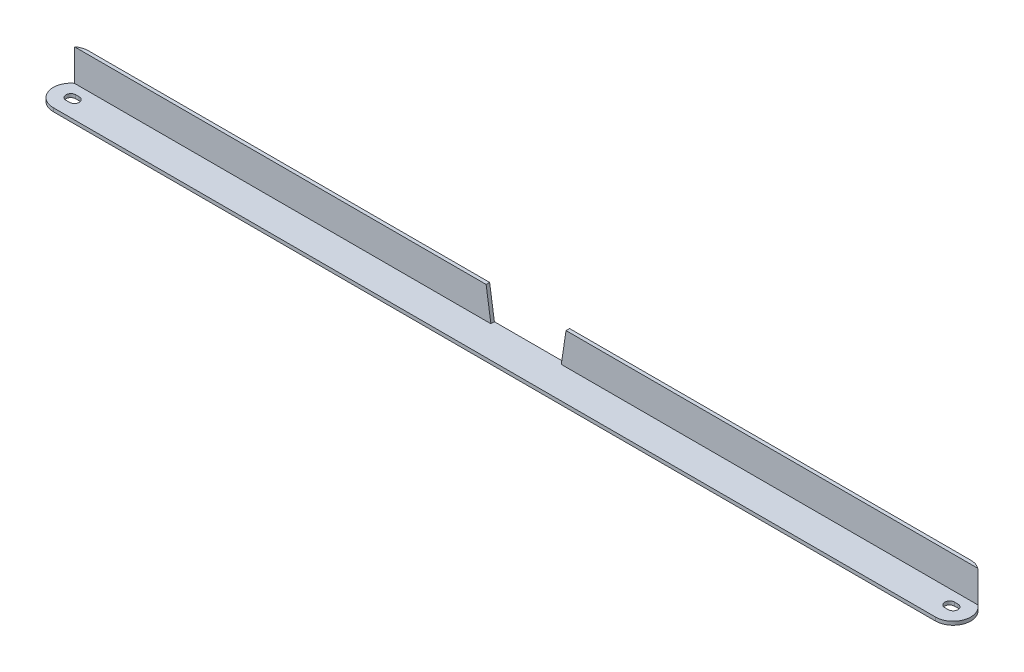
SolidWorks part; units mm, degrees
ref_plane "Front Plane" through (0, 0, 0) normal (0, 0, 1) x (1, 0, 0)
ref_plane "Top Plane" through (0, 0, 0) normal (0, 1, 0) x (1, 0, 0)
ref_plane "Right Plane" through (0, 0, 0) normal (1, 0, 0) x (0, 0, -1)
sketch "Sketch1" plane through (0, 0, 0) normal (1, 0, 0) x (0, 0, -1)
  line L0 (8, 10) -> (10, 10)
  line L1 (-10, 10) -> (10, 10) construction
  line L2 (-10, 10) -> (-10, -10) construction
  line L3 (-10, -10) -> (10, -10)
  line L4 (10, 10) -> (10, -10)
  line L5 (-10, 10) -> (10, -10) construction
  line L6 (-10, -10) -> (10, 10) construction
  line L7 (-10, 10) -> (8, 10) construction
  line L8 (-10, 10) -> (-10, -8) construction
  line L9 (-10, -8) -> (8, -8)
  line L10 (8, 10) -> (8, -8)
  line L11 (-10, -8) -> (-10, -10)
  point P0 (0, 0)
  dimension "D1" = 20
  dimension "D2" = 20
  dimension "D3" = 2
extrude "Boss-Extrude1" add sketch "Sketch1" along normal mid plane 540
sketch "Sketch2" plane through (0, 0, 0) normal (0, 1, 0) x (1, 0, 0)
  line L0 (0, 0) -> (249.65, 0) construction
  line L1 (248.65, 0) -> (250.65, 0) construction
  line L2 (250.65, -10) -> (270, -10)
  line L3 (248.65, 2.75) -> (250.65, 2.75)
  line L4 (248.65, -2.75) -> (250.65, -2.75)
  line L7 (270, 8) -> (270, -10) construction
  line L8 (270, -10) -> (270, 10)
  line L9 (270, 10) -> (250.65, 10)
  arc A0 (248.65, 2.75) -> (248.65, -2.75) centre (248.65, 0) ccw
  arc A1 (250.65, -2.75) -> (250.65, 2.75) centre (250.65, 0) ccw
  arc A2 (250.65, -10) -> (250.65, 10) centre (250.65, 0) ccw
  point P7 (249.65, 0)
  dimension "D1" = 249.65
  dimension "D2" = 2
extrude "Cut-Extrude1" cut sketch "Sketch2" against normal through all both and the other way through all contours L3 A1 L4 A0 | A2 L9 L8 L2
mirror "Mirror1" about plane through (0, 0, 0) normal (1, 0, 0) of "Cut-Extrude1"
sketch "Sketch3" plane through (0, 0, -8) normal (0, 0, 1) x (1, 0, 0)
  line L0 (-20, -8) -> (20, -8)
  line L1 (256.65, -8) -> (-256.65, -8) construction
  line L2 (20, -8) -> (22.706, 10)
  line L3 (256.65, 10) -> (-256.65, 10) construction
  line L4 (22.706, 10) -> (-22.706, 10)
  line L5 (0, -11) -> (0, 11) construction
  line L6 (-20, -8) -> (-22.706, 10)
  point P11 (0, 10)
  point P12 (0, -8)
  dimension "D1" = 20
extrude "Cut-Extrude2" cut sketch "Sketch3" against normal through all
equation "\"D1@Sketch3\"=\"w\""
equation "\"D2@Sketch1\"=\"w\""
equation "\"D1@Sketch1\"=\"w\""
equation "\"t\"= 2"
equation "\"w\"= 20"
equation "\"D3@Sketch1\"=\"t\""
